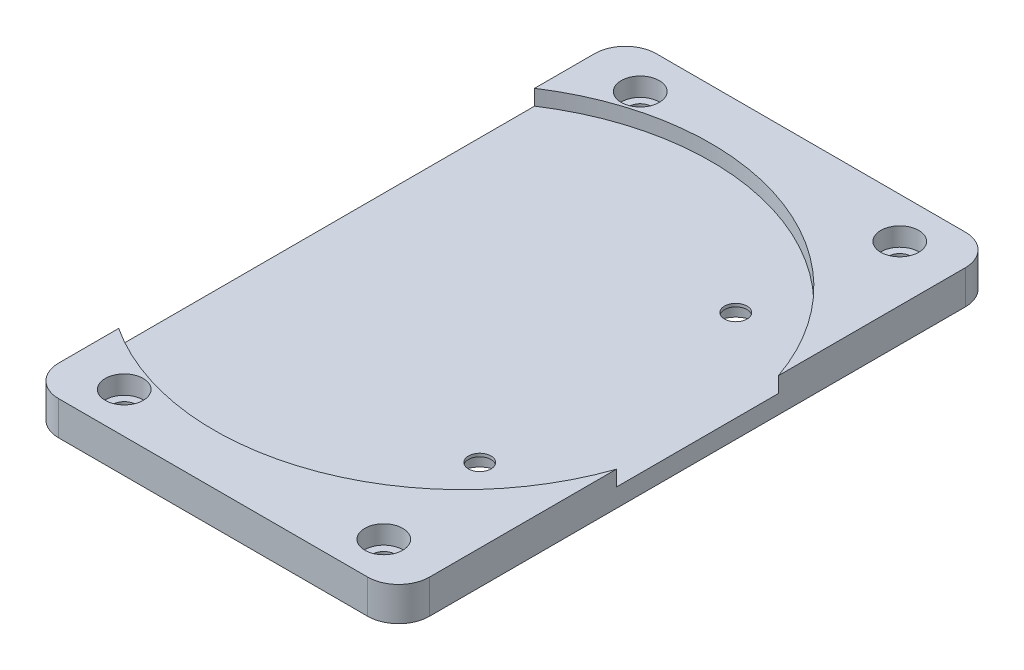
SolidWorks part; units mm, degrees
ref_plane "Alzado" through (0, 0, 0) normal (0, 0, 1) x (1, 0, 0)
ref_plane "Planta" through (0, 0, 0) normal (0, 1, 0) x (1, 0, 0)
ref_plane "Vista lateral" through (0, 0, 0) normal (1, 0, 0) x (0, 0, -1)
sketch "Croquis2" plane through (0, 0, 0) normal (0, 1, 0) x (1, 0, 0)
  line L0 (30, 96.7) -> (30, 0) construction
  line L1 (0, 0) -> (60, 0)
  line L2 (0, 0) -> (0, 96.7)
  line L3 (0, 96.7) -> (60, 96.7)
  line L4 (60, 0) -> (60, 96.7)
  line L5 (0, 48.35) -> (60, 48.35) construction
  line L6 (9, 6.6) -> (51, 6.6) construction
  line L7 (9, 90.1) -> (51, 90.1) construction
  line L8 (9, 90.1) -> (9, 6.6) construction
  circle A0 centre (9, 6.6) radius 1.825
  circle A1 centre (51, 6.6) radius 1.825
  circle A2 centre (9, 90.1) radius 1.825
  circle A3 centre (51, 90.1) radius 1.825
  point P15 (30, 6.6)
  dimension "D3" = 3.65
  dimension "D4" = 3.65
  dimension "D1" = 96.7
  dimension "D2" = 60
  dimension "D5" = 42
  dimension "D6" = 83.5
extrude "Saliente-Extruir1" add sketch "Croquis2" along normal blind 5.5
fillet "Redondeo2" radius 5 4 edges at (0, 2.75, -96.7) (60, 2.75, -96.7) (60, 2.75, 0) (0, 2.75, 0)
sketch "Croquis3" plane through (0, 5.5, 0) normal (0, 1, 0) x (1, 0, 0)
  line L0 (0, 48.35) -> (60, 48.35) construction
  line L1 (0, 91.7) -> (0, 5) construction
  line L2 (60, 5) -> (60, 91.7) construction
  line L3 (5, 0) -> (55, 0) construction
  circle A0 centre (22, 48.35) radius 38 construction
  dimension "D1" = 76
  dimension "D2" = 48.35
sketch "Croquis4" plane through (0, 5.5, 0) normal (0, 1, 0) x (1, 0, 0)
  circle A0 centre (22, 48.35) radius 39.5
  circle A1 centre (22, 48.35) radius 38 construction
  dimension "D1" = 1.5
extrude "Cortar-Extruir1" cut sketch "Croquis4" against normal blind 2.5
sketch "Croquis5" plane through (0, 3, 0) normal (0, 1, 0) x (1, 0, 0)
  line L2 (30, 96.7) -> (30, 0) construction
  line L3 (55, 96.7) -> (5, 96.7) construction
  line L4 (5, 0) -> (55, 0) construction
  circle A0 centre (45.2114, 69.3522) radius 1.825
  circle A1 centre (45.4975, 27.6339) radius 1.825
  dimension "D1" = 3.65
  dimension "D2" = 3.65
extrude "Cortar-Extruir2" cut sketch "Croquis5" against normal through all
sketch "Croquis6" plane through (0, 0, 0) normal (0, -1, 0) x (1, 0, 0)
  circle A0 centre (45.4975, -27.6339) radius 3.325
  circle A1 centre (45.2114, -69.3522) radius 3.325
  circle A2 centre (45.4975, -27.6339) radius 1.825 construction
  circle A3 centre (45.2114, -69.3522) radius 1.825 construction
  dimension "D1" = 1.5
  dimension "D2" = 1.5
extrude "Cortar-Extruir3" cut sketch "Croquis6" against normal blind 2.5
sketch "Croquis7" plane through (0, 5.5, 0) normal (0, 1, 0) x (1, 0, 0)
  line L0 (30, 96.7) -> (30, 0) construction
  line L1 (55, 96.7) -> (5, 96.7) construction
  line L2 (5, 0) -> (55, 0) construction
  line L3 (0, 48.35) -> (60, 48.35) construction
  circle A0 centre (51, 90.1) radius 3.075
  circle A1 centre (9, 90.1) radius 3.075
  circle A2 centre (51, 6.6) radius 3.075
  circle A3 centre (9, 6.6) radius 3.075
  dimension "D1" = 6.15
extrude "Cortar-Extruir4" cut sketch "Croquis7" against normal blind 3
sketch "Croquis10" plane through (0, 5.5, 0) normal (0, 1, 0) x (1, 0, 0)
  circle A0 centre (22, 48.35) radius 40.2
  arc A1 (60, 59.1319) -> (0, 81.1562) centre (22, 48.35) ccw construction
  dimension "D1" = 0.7
extrude "Cortar-Extruir5" cut sketch "Croquis10" against normal up to surface (2.5 mm away) up to face at (45.2114, 3, -67.5272)
